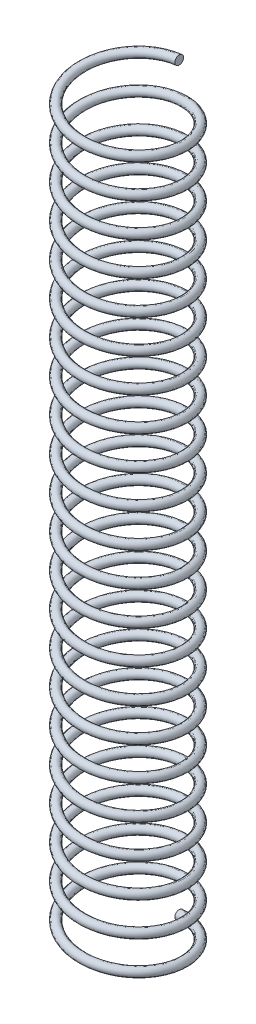
SolidWorks part; units mm, degrees
material "1060 Alloy"
ref_plane "Front Plane" through (0, 0, 0) normal (0, 0, 1) x (1, 0, 0)
ref_plane "Top Plane" through (0, 0, 0) normal (0, 1, 0) x (1, 0, 0)
ref_plane "Right Plane" through (0, 0, 0) normal (1, 0, 0) x (0, 0, -1)
sketch "Sketch1" plane through (0, 0, 0) normal (0, 1, 0) x (1, 0, 0)
  circle A0 centre (0, 0) radius 7
  dimension "D1" = 14
curve "Helix/Spiral1" pitch 4.6 height 101.2 turns 22
sketch "Sketch3" plane through (0, 0, 0) normal (1, 0, 0) x (0, 0, -1)
  circle A0 centre (7, 0) radius 0.6
  dimension "D1" = 1.2
  dimension "D2" = 7
sweep "Sweep1" add profiles "Sketch3" path "Helix/Spiral1"
